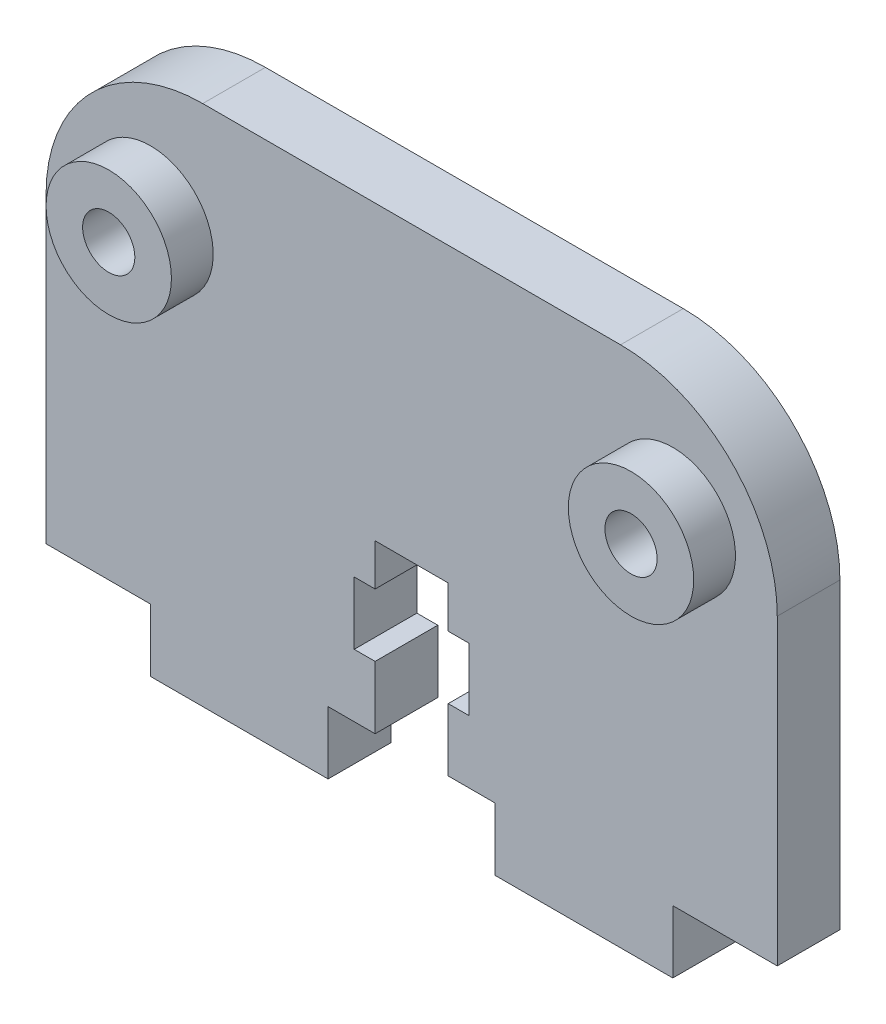
SolidWorks part; units mm, degrees
ref_plane "Plan de face" through (0, 0, 0) normal (0, 0, 1) x (1, 0, 0)
ref_plane "Plan de dessus" through (0, 0, 0) normal (0, 1, 0) x (1, 0, 0)
ref_plane "Plan de droite" through (0, 0, 0) normal (1, 0, 0) x (0, 0, -1)
sketch "Esquisse1" plane through (0, 0, 0) normal (0, 0, 1) x (1, 0, 0)
  line L1 (0, 0) -> (35, 0)
  line L2 (0, 0) -> (0, 25)
  line L3 (0, 25) -> (35, 25)
  line L4 (35, 0) -> (35, 25)
  dimension "D1" = 25
  dimension "D2" = 35
extrude "Boss.-Extru.1" add sketch "Esquisse1" along normal blind 3
fillet "Congé3" radius 7.5 2 edges at (35, 25, 1.5) (0, 25, 1.5)
sketch "Esquisse3" plane through (0, 0, 3) normal (0, 0, 1) x (1, 0, 0)
  line L0 (0, 0) -> (35, 0) construction
  line L1 (13.5, 0) -> (21.5, 0)
  line L2 (13.5, 0) -> (13.5, 3)
  line L3 (13.5, 3) -> (21.5, 3)
  line L4 (21.5, 0) -> (21.5, 3)
  line L5 (0, 17.5) -> (0, 0) construction
  point P6 (17.5, 0)
  dimension "D1" = 8
  dimension "D2" = 3
  dimension "D3" = 17.5
extrude "Enlèv. mat.-Extru.2" cut sketch "Esquisse3" against normal up to next contours L3 L4 L1 L2
sketch "Esquisse4" plane through (0, 0, 3) normal (0, 0, 1) x (1, 0, 0)
  line L0 (0, 17.5) -> (0, 0) construction
  line L1 (14.75, 9) -> (20.25, 9)
  line L2 (14.75, 9) -> (14.75, 6)
  line L3 (14.75, 6) -> (20.25, 6)
  line L4 (20.25, 9) -> (20.25, 6)
  line L5 (27.5, 25) -> (7.5, 25) construction
  point P4 (17.5, 6)
  dimension "D1" = 5.5
  dimension "D2" = 3
  dimension "D3" = 17.5
  dimension "D4" = 16
extrude "Enlèv. mat.-Extru.3" cut sketch "Esquisse4" against normal up to next
sketch "Esquisse5" plane through (0, 0, 3) normal (0, 0, 1) x (1, 0, 0)
  line L1 (15.75, 11) -> (19.25, 11)
  line L2 (15.75, 11) -> (15.75, 0)
  line L3 (15.75, 0) -> (19.25, 0)
  line L4 (19.25, 11) -> (19.25, 0)
  point P4 (17.5, 0)
  dimension "D1" = 17.5
  dimension "D2" = 11
  dimension "D3" = 3.5
extrude "Enlèv. mat.-Extru.4" cut sketch "Esquisse5" against normal up to next contours L1 L4 L3 L2
sketch "Esquisse8" plane through (0, 0, 3) normal (0, 0, 1) x (1, 0, 0)
  line L1 (0, 0) -> (5, 0)
  line L2 (0, 0) -> (0, 3)
  line L3 (0, 3) -> (5, 3)
  line L4 (5, 0) -> (5, 3)
  dimension "D1" = 5
  dimension "D2" = 3
extrude "Enlèv. mat.-Extru.7" cut sketch "Esquisse8" against normal up to next
sketch "Esquisse9" plane through (0, 0, 3) normal (0, 0, 1) x (1, 0, 0)
  line L1 (35, 0) -> (30, 0)
  line L2 (35, 0) -> (35, 3)
  line L3 (35, 3) -> (30, 3)
  line L4 (30, 0) -> (30, 3)
  dimension "D1" = 5
  dimension "D2" = 3
extrude "Enlèv. mat.-Extru.8" cut sketch "Esquisse9" against normal up to next contours L3 L4 L1 L2
sketch "Esquisse12" plane through (0, 0, 3) normal (0, 0, 1) x (1, 0, 0)
  line L0 (35, 3) -> (35, 17.5) construction
  line L1 (27.5, 25) -> (7.5, 25) construction
  circle A0 centre (30, 19) radius 3
  dimension "D1" = 6
  dimension "D2" = 5
  dimension "D3" = 6
extrude "Boss.-Extru.2" add sketch "Esquisse12" along normal blind 2 contours A0
sketch "Esquisse13" plane through (0, 0, 3) normal (0, 0, 1) x (1, 0, 0)
  line L2 (27.5, 25) -> (7.5, 25) construction
  line L3 (0, 17.5) -> (0, 3) construction
  circle A1 centre (5, 19) radius 3
  dimension "D1" = 6
  dimension "D2" = 6
  dimension "D3" = 5
extrude "Boss.-Extru.4" add sketch "Esquisse13" along normal blind 2 contours A1
sketch "Esquisse14" plane through (0, 0, 5) normal (0, 0, 1) x (1, 0, 0)
  line L0 (27.5, 25) -> (7.5, 25) construction
  line L1 (0, 17.5) -> (0, 3) construction
  circle A0 centre (5, 19) radius 1.25
  dimension "D1" = 2.5
  dimension "D2" = 6
  dimension "D3" = 5
extrude "Enlèv. mat.-Extru.11" cut sketch "Esquisse14" against normal up to next
sketch "Esquisse15" plane through (0, 0, 5) normal (0, 0, 1) x (1, 0, 0)
  line L0 (35, 3) -> (35, 17.5) construction
  line L1 (27.5, 25) -> (7.5, 25) construction
  circle A0 centre (30, 19) radius 1.25
  dimension "D1" = 2.5
  dimension "D2" = 5
  dimension "D3" = 6
extrude "Enlèv. mat.-Extru.12" cut sketch "Esquisse15" against normal up to next contours A0
